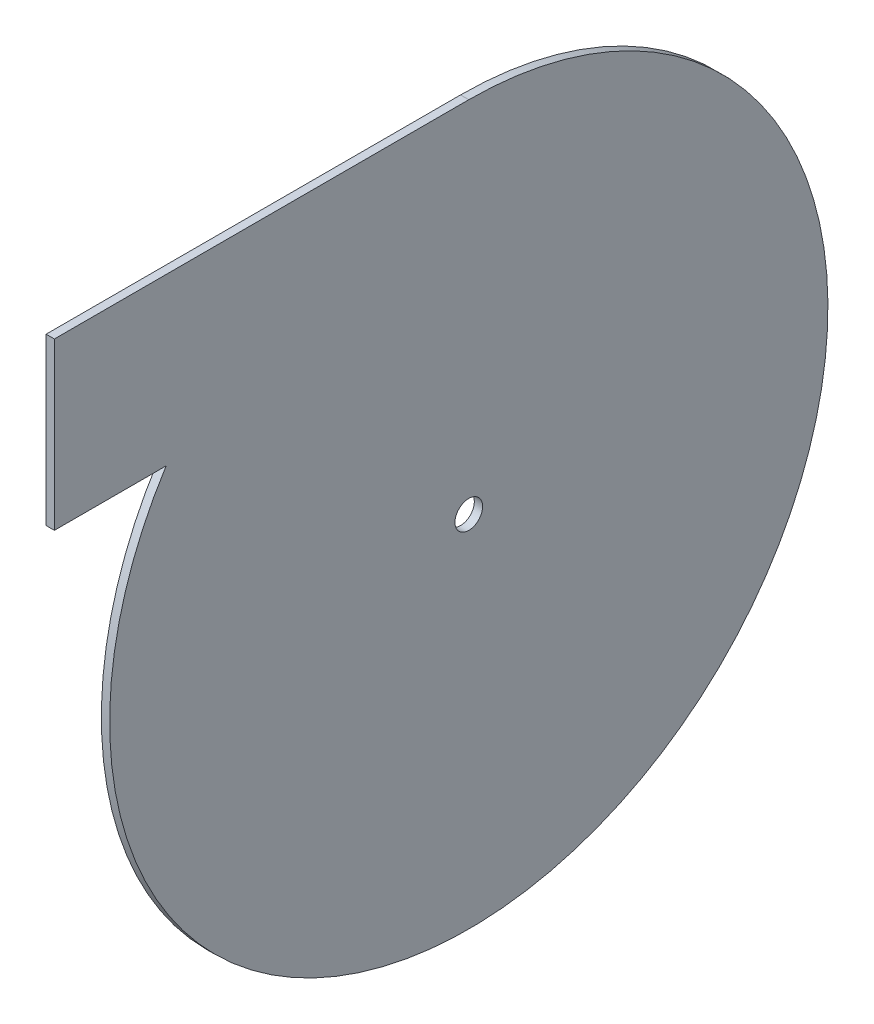
SolidWorks part; units mm, degrees
ref_plane "Front Plane" through (0, 0, 0) normal (0, 0, 1) x (1, 0, 0)
ref_plane "Top Plane" through (0, 0, 0) normal (0, 1, 0) x (1, 0, 0)
ref_plane "Right Plane" through (0, 0, 0) normal (1, 0, 0) x (0, 0, -1)
sketch "Sketch1" plane through (0, 0, 0) normal (1, 0, 0) x (0, 0, -1)
  line L0 (0, 130) -> (-150, 130)
  line L1 (-150, 130) -> (-150, 70)
  line L2 (-150, 70) -> (-109.5445, 70)
  arc A0 (-109.5445, 70) -> (0, 130) centre (0, 0) ccw
  circle A1 centre (0, 0) radius 5
  dimension "D1" = 260
  dimension "D2" = 10
  dimension "D3" = 60
  dimension "D4" = 150
extrude "Boss-Extrude1" add sketch "Sketch1" along normal blind 3
